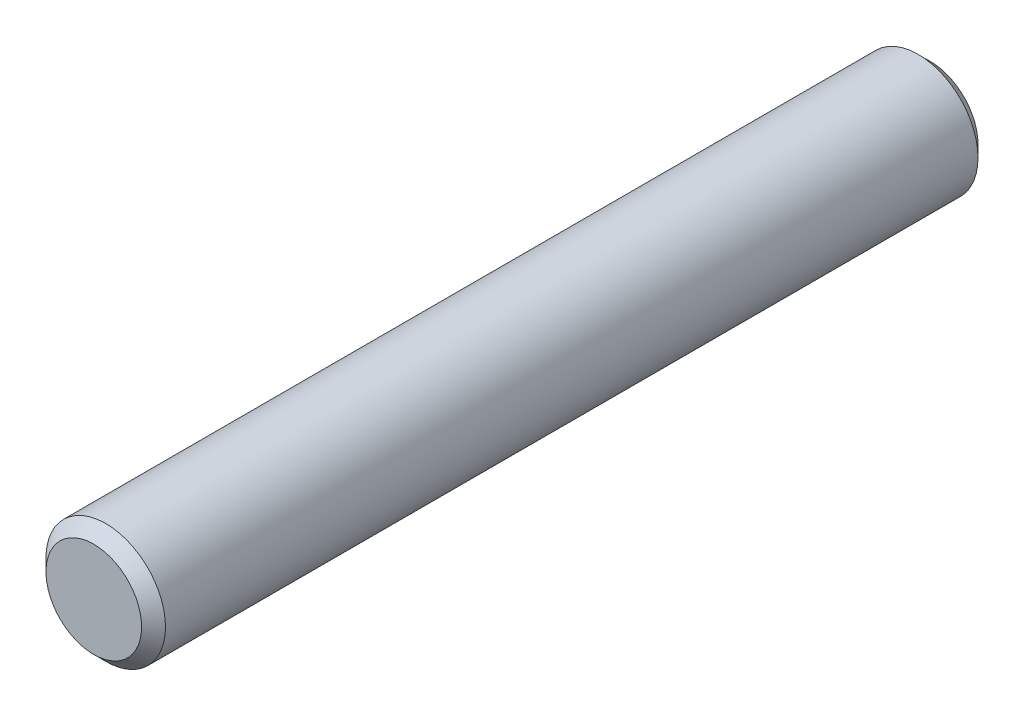
SolidWorks part; units mm, degrees
ref_plane "Piano frontale" through (0, 0, 0) normal (0, 0, 1) x (1, 0, 0)
ref_plane "Piano superiore" through (0, 0, 0) normal (0, 1, 0) x (1, 0, 0)
ref_plane "Piano destro" through (0, 0, 0) normal (1, 0, 0) x (0, 0, -1)
sketch "Schizzo1" plane through (0, 0, 0) normal (0, 0, 1) x (1, 0, 0)
  circle A0 centre (0, 0) radius 5
  dimension "D1" = 10
extrude "Estrusione-Estrusione1" add sketch "Schizzo1" along normal blind 70
chamfer "Smusso1" distance 1 angle 45 2 edges at (5, 0, 0) (5, 0, 70)
